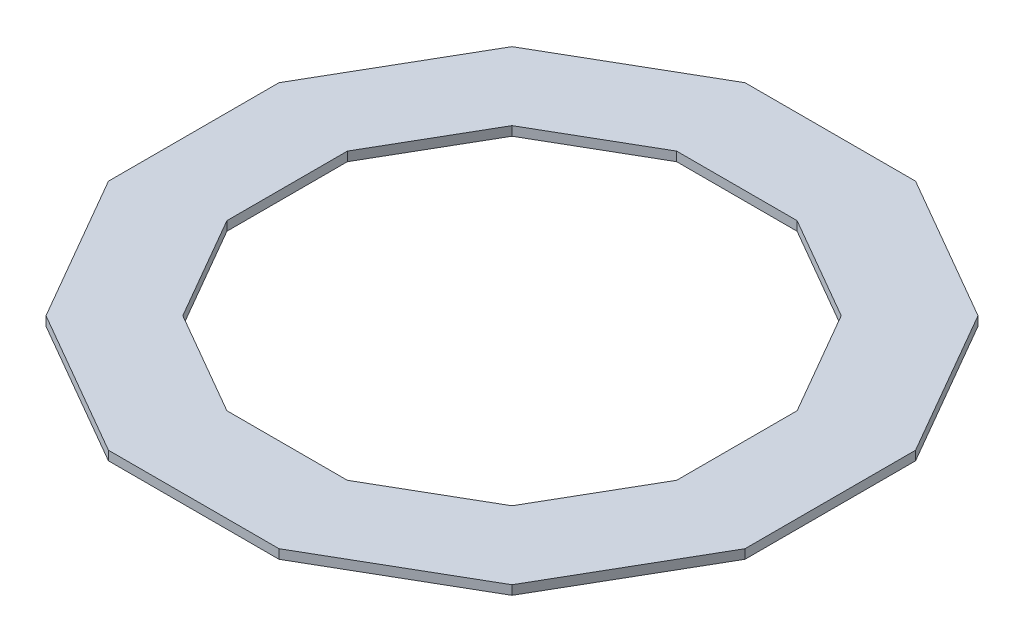
SolidWorks part; units mm, degrees
material "ABS PC"
ref_plane "Front Plane" through (0, 0, 0) normal (0, 0, 1) x (1, 0, 0)
ref_plane "Top Plane" through (0, 0, 0) normal (0, 1, 0) x (1, 0, 0)
ref_plane "Right Plane" through (0, 0, 0) normal (1, 0, 0) x (0, 0, -1)
sketch "Sketch1" plane through (0, 0, 0) normal (0, 1, 0) x (1, 0, 0)
  line L0 (26.296, 98.1381) -> (-26.296, 98.1381)
  line L1 (-26.296, 98.1381) -> (-71.842, 71.842)
  line L2 (-71.842, 71.842) -> (-98.1381, 26.296)
  line L3 (-98.1381, 26.296) -> (-98.1381, -26.296)
  line L4 (-98.1381, -26.296) -> (-71.842, -71.842)
  line L5 (-71.842, -71.842) -> (-26.296, -98.1381)
  line L6 (-26.296, -98.1381) -> (26.296, -98.1381)
  line L7 (26.296, -98.1381) -> (71.842, -71.842)
  line L8 (71.842, -71.842) -> (98.1381, -26.296)
  line L9 (98.1381, -26.296) -> (98.1381, 26.296)
  line L10 (98.1381, 26.296) -> (71.842, 71.842)
  line L11 (71.842, 71.842) -> (26.296, 98.1381)
  circle A0 centre (0, 0) radius 101.6
  dimension "D1" = 203.2
extrude "Boss-Extrude1" add sketch "Sketch1" against normal blind 2.921 contours L10 L11 L0 L1 L2 L3 L4 L5 L6 L7 L8 L9
sketch "Sketch3" plane through (0, 0, 0) normal (0, 1, 0) x (1, 0, 0)
  line L12 (-52.2651, 52.2651) -> (-19.1304, 71.3954)
  line L13 (-19.1304, 71.3954) -> (19.1304, 71.3954)
  line L14 (19.1304, 71.3954) -> (52.2651, 52.2651)
  line L15 (52.2651, 52.2651) -> (71.3954, 19.1304)
  line L16 (71.3954, 19.1304) -> (71.3954, -19.1304)
  line L17 (71.3954, -19.1304) -> (52.2651, -52.2651)
  line L18 (52.2651, -52.2651) -> (19.1304, -71.3954)
  line L19 (19.1304, -71.3954) -> (-19.1304, -71.3954)
  line L20 (-19.1304, -71.3954) -> (-52.2651, -52.2651)
  line L21 (-52.2651, -52.2651) -> (-71.3954, -19.1304)
  line L22 (-71.3954, -19.1304) -> (-71.3954, 19.1304)
  line L23 (-71.3954, 19.1304) -> (-52.2651, 52.2651)
  line L24 (-71.842, 71.842) -> (-98.1381, 26.296) construction
  line L25 (-26.296, 98.1381) -> (-71.842, 71.842) construction
  line L26 (26.296, 98.1381) -> (-26.296, 98.1381) construction
  line L27 (71.842, 71.842) -> (26.296, 98.1381) construction
  line L28 (98.1381, 26.296) -> (71.842, 71.842) construction
  line L29 (98.1381, -26.296) -> (98.1381, 26.296) construction
  line L30 (71.842, -71.842) -> (98.1381, -26.296) construction
  line L31 (26.296, -98.1381) -> (71.842, -71.842) construction
  line L32 (-26.296, -98.1381) -> (26.296, -98.1381) construction
  line L33 (-71.842, -71.842) -> (-26.296, -98.1381) construction
  line L34 (-98.1381, -26.296) -> (-71.842, -71.842) construction
  line L35 (-98.1381, 26.296) -> (-98.1381, -26.296) construction
  line L36 (-26.296, 98.1381) -> (26.296, -98.1381) construction
  line L37 (26.296, 98.1381) -> (-26.296, -98.1381) construction
  circle A0 centre (0, 0) radius 73.914
  dimension "D1" = 147.828
extrude "Cut-Extrude1" cut sketch "Sketch3" against normal through all contours L23 L22 L21 L20 L19 L18 L17 L16 L15 L14 L13 L12
sketch "Sketch4" plane through (0, 0, 0) normal (0, 1, 0) x (1, 0, 0)
  line L24 (101.0591, 27.0787) -> (73.9804, 73.9804)
  line L25 (73.9804, 73.9804) -> (27.0787, 101.0591)
  line L26 (27.0787, 101.0591) -> (-27.0787, 101.0591)
  line L27 (-27.0787, 101.0591) -> (-73.9804, 73.9804)
  line L28 (-73.9804, 73.9804) -> (-101.0591, 27.0787)
  line L29 (-101.0591, 27.0787) -> (-101.0591, -27.0787)
  line L30 (-101.0591, -27.0787) -> (-73.9804, -73.9804)
  line L31 (-73.9804, -73.9804) -> (-27.0787, -101.0591)
  line L32 (-27.0787, -101.0591) -> (27.0787, -101.0591)
  line L33 (27.0787, -101.0591) -> (73.9804, -73.9804)
  line L34 (73.9804, -73.9804) -> (101.0591, -27.0787)
  line L35 (101.0591, -27.0787) -> (101.0591, 27.0787)
  line L36 (101.0591, 27.0787) -> (73.9804, 73.9804)
  line L37 (73.9804, 73.9804) -> (27.0787, 101.0591)
  line L38 (27.0787, 101.0591) -> (-27.0787, 101.0591)
  line L39 (-27.0787, 101.0591) -> (-73.9804, 73.9804)
  line L40 (-73.9804, 73.9804) -> (-101.0591, 27.0787)
  line L41 (-101.0591, 27.0787) -> (-101.0591, -27.0787)
  line L42 (-101.0591, -27.0787) -> (-73.9804, -73.9804)
  line L43 (-73.9804, -73.9804) -> (-27.0787, -101.0591)
  line L44 (-27.0787, -101.0591) -> (27.0787, -101.0591)
  line L45 (27.0787, -101.0591) -> (73.9804, -73.9804)
  line L46 (73.9804, -73.9804) -> (101.0591, -27.0787)
  line L47 (101.0591, -27.0787) -> (101.0591, 27.0787)
  line L60 (98.1381, 26.296) -> (71.842, 71.842)
  line L61 (71.842, 71.842) -> (26.296, 98.1381)
  line L62 (26.296, 98.1381) -> (-26.296, 98.1381)
  line L63 (-26.296, 98.1381) -> (-71.842, 71.842)
  line L64 (-71.842, 71.842) -> (-98.1381, 26.296)
  line L65 (-98.1381, 26.296) -> (-98.1381, -26.296)
  line L66 (-98.1381, -26.296) -> (-71.842, -71.842)
  line L67 (-71.842, -71.842) -> (-26.296, -98.1381)
  line L68 (-26.296, -98.1381) -> (26.296, -98.1381)
  line L69 (26.296, -98.1381) -> (71.842, -71.842)
  line L70 (71.842, -71.842) -> (98.1381, -26.296)
  line L71 (98.1381, -26.296) -> (98.1381, 26.296)
  line L72 (98.1381, 26.296) -> (71.842, 71.842)
  line L73 (71.842, 71.842) -> (26.296, 98.1381)
  line L74 (26.296, 98.1381) -> (-26.296, 98.1381)
  line L75 (-26.296, 98.1381) -> (-71.842, 71.842)
  line L76 (-71.842, 71.842) -> (-98.1381, 26.296)
  line L77 (-98.1381, 26.296) -> (-98.1381, -26.296)
  line L78 (-98.1381, -26.296) -> (-71.842, -71.842)
  line L79 (-71.842, -71.842) -> (-26.296, -98.1381)
  line L80 (-26.296, -98.1381) -> (26.296, -98.1381)
  line L81 (26.296, -98.1381) -> (71.842, -71.842)
  line L82 (71.842, -71.842) -> (98.1381, -26.296)
  line L83 (98.1381, -26.296) -> (98.1381, 26.296)
  dimension "D1" = 2.921
  dimension "D2" = 0
extrude "Boss-Extrude2" add sketch "Sketch4" against normal up to surface (2.921 mm away) up to face at (0, -2.921, 0)
